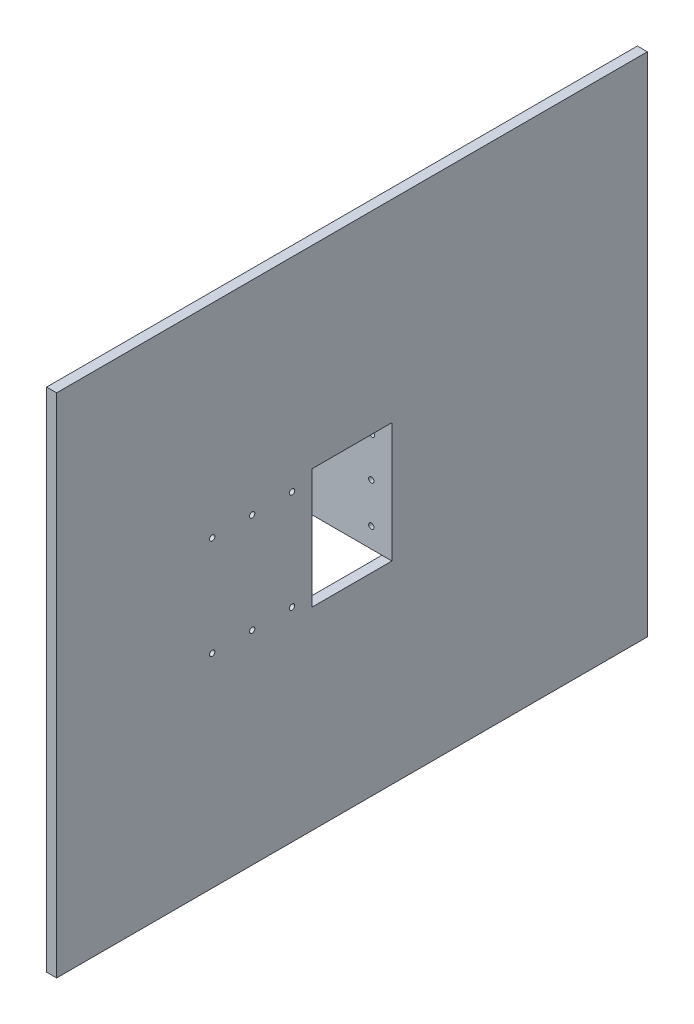
SolidWorks part; units mm, degrees
ref_plane "前视基准面" through (0, 0, 0) normal (0, 0, 1) x (1, 0, 0)
ref_plane "上视基准面" through (0, 0, 0) normal (0, 1, 0) x (1, 0, 0)
ref_plane "右视基准面" through (0, 0, 0) normal (1, 0, 0) x (0, 0, -1)
sketch "草图1" plane through (0, 0, 0) normal (0, 0, 1) x (1, 0, 0)
  line L0 (0, 102.6959) -> (0, -109.4745) construction
  line L1 (-90, -90) -> (90, -90)
  line L2 (-90, -90) -> (-90, 90)
  line L3 (-90, 90) -> (90, 90)
  line L4 (90, -90) -> (90, 90)
  line L5 (-90, -90) -> (90, 90) construction
  line L6 (-90, 90) -> (90, -90) construction
  circle A0 centre (-75, 60) radius 4
  circle A1 centre (-74.0356, 0) radius 4
  circle A2 centre (-74.0356, -60) radius 4
  circle A3 centre (74.0356, -60) radius 4
  circle A4 centre (74.0356, 0) radius 4
  circle A5 centre (75, 60) radius 4
  point P0 (0, 0)
  dimension "D4" = 8
  dimension "D7" = 8
  dimension "D9" = 8
  dimension "D1" = 180
  dimension "D2" = 180
  dimension "D3" = 15
  dimension "D5" = 30
  dimension "D6" = 60
  dimension "D8" = 60
extrude "凸台-拉伸1" add sketch "草图1" along normal blind 15
sketch "草图9" plane through (90, 0, 0) normal (1, 0, 0) x (0, 0, -1)
  line L0 (-210, -115.8159) -> (-210, -168.9159) construction
  line L1 (-135, -90) -> (-15, -90)
  line L2 (-135, -90) -> (-135, 90)
  line L3 (-135, 90) -> (-15, 90)
  line L4 (-15, -90) -> (-15, 90)
  line L5 (-135, -90) -> (-15, 90) construction
  line L6 (-135, 90) -> (-15, -90) construction
  line L7 (-518.7791, -380.7161) -> (368.7791, -380.7161)
  line L8 (63.4226, 0) -> (-553.6129, 0) construction
  line L9 (-518.7791, -380.7161) -> (-518.7791, 380.7161)
  line L10 (-518.7791, 380.7161) -> (368.7791, 380.7161)
  line L11 (368.7791, -380.7161) -> (368.7791, 380.7161)
  line L12 (-518.7791, -380.7161) -> (368.7791, 380.7161) construction
  line L13 (-518.7791, 380.7161) -> (368.7791, -380.7161) construction
  circle A1 centre (-165, 75) radius 4
  circle A3 centre (-225, 75) radius 4
  circle A4 centre (-285, 75) radius 4
  circle A5 centre (-285, -75) radius 4
  circle A6 centre (-225, -75) radius 4
  circle A7 centre (-165, -75) radius 4
  point P0 (-75, 0)
  point P6 (-75, 0)
  dimension "D7" = 8
  dimension "D4" = 8
  dimension "D5" = 8
  dimension "D1" = 120
  dimension "D2" = 180
  dimension "D10" = 75
  dimension "D11" = 30
  dimension "D12" = 60
  dimension "D13" = 60
  dimension "D14" = 15
extrude "凸台-拉伸2" add sketch "草图9" along normal blind 15
